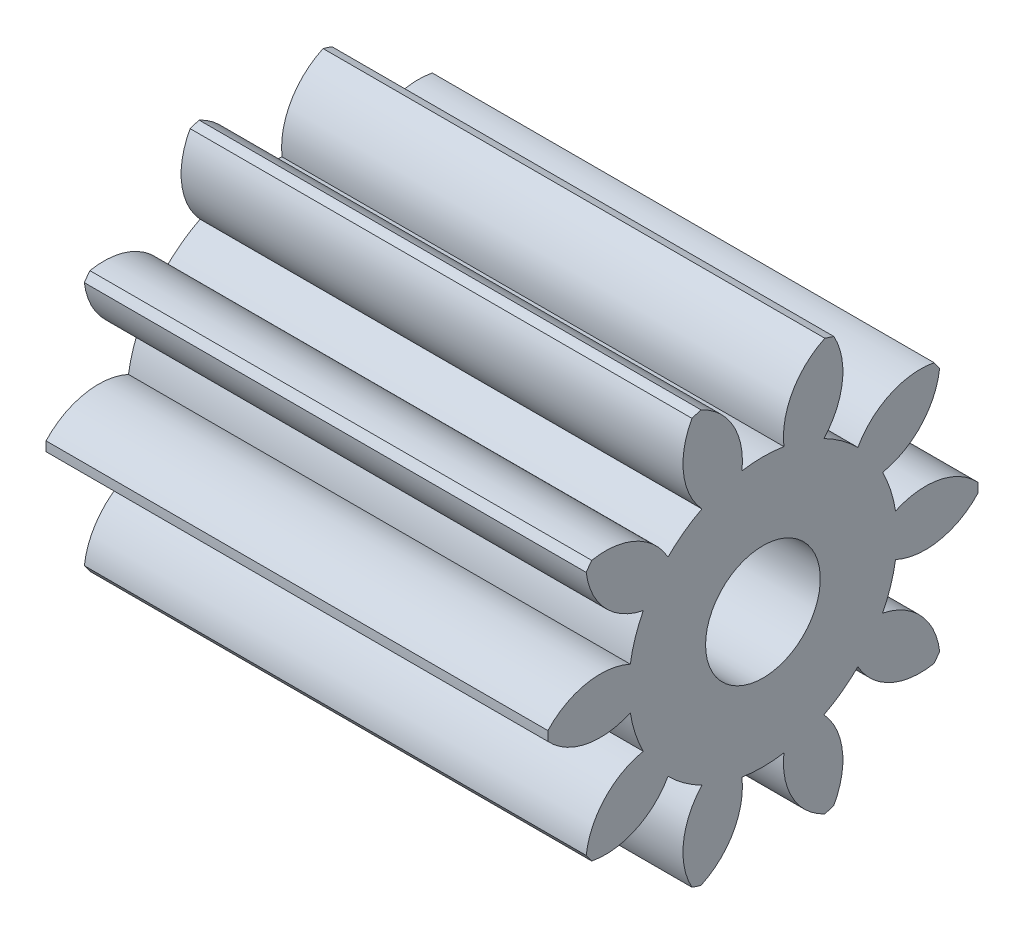
SolidWorks part; units mm, degrees
material "Простая углеродистая сталь"
ref_plane "Plane1" through (0, 0, 0) normal (0, 0, 1) x (1, 0, 0)
ref_plane "Plane2" through (0, 0, 0) normal (0, 1, 0) x (1, 0, 0)
ref_plane "Plane3" through (0, 0, 0) normal (1, 0, 0) x (0, 0, -1)
sketch "HoldingSke" plane through (0, 0, 0) normal (0, 1, 0) x (1, 0, 0)
  line L0 (0, 0) -> (3.9392, -0.6946)
  line L1 (-15, 0) -> (100, 0) construction
  line L2 (0, 0) -> (-2.1039, 2.3779)
  line L3 (0, 0) -> (-11.863, 4.5341)
  line L4 (0, 0) -> (8.5048, 1.4996)
  line L5 (0, 0) -> (-46.8476, -17.4728)
  line L6 (0, 0) -> (-2.9014, -1.9576)
  line L7 (-2.1039, 2.3779) -> (8.6586, 51.2059)
  line L8 (-76.2, 54.61) -> (-76.1, 54.61)
  line L9 (-71.009, 38.7566) -> (-53.1078, 45.2721)
  line L10 (-76.2, 71.12) -> (104.1128, 71.12)
  line L11 (0, 0) -> (-3.5, 0)
  line L12 (-76.2, 101.6) -> (-76.192, 101.6)
  line L13 (24.9733, 27.94) -> (52.9518, 28.4284)
  line L14 (24.9733, 27.94) -> (24.9743, 27.94)
  line L15 (24.9733, 27.94) -> (100.4006, 29.5858)
  line L16 (-63.627, -0.25) -> (-12.827, -0.25)
  circle A0 centre (0, 0) radius 0.4
  circle A1 centre (0, 0) radius 0.9365
  circle A2 centre (0, 0) radius 37.5
  circle A3 centre (0, 0) radius 0.4
  dimension "MHD" = 1.873
  dimension "Hub_dia" = 75
  dimension "Bore" = 0.8
  dimension "MBD" = 0.8
  dimension "Num_teeth" = 10
  dimension "Pitch" = 4
  dimension "Overall_len" = 50
  dimension "Show_teeth" = 10
  dimension "Thickness" = 3.5
  dimension "OAL" = 50.0001
  dimension "T_dim" = 0.1
  dimension "Ap" = 20
  dimension "H" = 19.05
  dimension "Pitch_radius" = 180.3128
  dimension "Width" = 3.5
  dimension "Backlash" = 0.008
  dimension "Addendum_fac" = 1
  dimension "Dedendum_fac" = 1.25
  dimension "Clearance_fac" = 0.25
  dimension "Dedendum_add" = 0.001
  dimension "Module" = 0.25
sketch "BasProSke" plane through (0, 0, 0) normal (0, 1, 0) x (1, 0, 0)
  line L0 (-10, 0) -> (60, 0) construction
  line L1 (0, 0) -> (0, 1.5)
  line L2 (0, 0) -> (3.5, 0)
  line L3 (3.5, 0) -> (3.5, 1.5)
  line L4 (3.5, 1.5) -> (0, 1.5)
  dimension "Thickness" = 3.5
  dimension "Diameter" = 3
revolve "Base-Revolve" add sketch "BasProSke" angle 360 about L0
sketch "TooCutSke" plane through (0, 0, 0) normal (1, 0, 0) x (0, 0, -1)
  line L1 (0, 0) -> (0, 107) construction
  line L2 (0, 0) -> (-0.2095, 1.2323) construction
  line L3 (0, 0) -> (-0.7644, 2.3524) construction
  line L4 (-0.2095, 1.2323) -> (-0.3822, 1.1762) construction
  arc A0 (0.1463, 0.925) -> (-0.1463, 0.925) centre (0, 0) ccw
  arc A1 (0.4686, 1.4516) -> (-0.4686, 1.4516) centre (0, 0) ccw
  circle A2 centre (0, 0) radius 1.25 construction
  circle A3 centre (0, 0) radius 1.1746 construction
  arc A4 (-0.1463, 0.925) -> (-0.4686, 1.4516) centre (-0.6429, 0.983) ccw
  arc A5 (0.4686, 1.4516) -> (0.1463, 0.925) centre (0.6429, 0.983) ccw
  dimension "Root_dia" = 1.873
  dimension "Overcut_dia" = 3.0508
  dimension "Pitch_dia" = 2.5
  dimension "Base_dia" = 2.3492
  dimension "Flank_rad" = 0.5
  dimension "Half_ang" = 18
  dimension "Half_CT" = 0.1815
extrude "ToothCut" cut sketch "TooCutSke" along normal through all
fillet "Breaks" [suppressed] radius 0.005
fillet "RootFillets" [suppressed] radius 0.0635
pattern_circular "TeethCuts" count 10 every 36 about axis through (-10, 0, 0) along (1, 0, 0) of "ToothCut", "RootFillets", "Breaks"
sketch "HubNeaOneSke" plane through (0, 0, 0) normal (-1, 0, 0) x (0, 0, 1)
  circle A0 centre (0, 0) radius 0.9365
  dimension "Diameter" = 1.873
extrude "HubNearOne" [suppressed] add sketch "HubNeaOneSke" along normal blind 46.5001
sketch "HubNeaBotSke" plane through (0, 0, 0) normal (-1, 0, 0) x (0, 0, 1)
  circle A0 centre (0, 0) radius 0.9365
  dimension "Diameter" = 1.873
extrude "HubNearBoth" [suppressed] add sketch "HubNeaBotSke" along normal blind 23.25
ref_plane "FarPln" through (3.5, 0, 0) normal (1, 0, 0) x (0, 0, -1)
sketch "HubFarSke" plane through (3.5, 0, 0) normal (1, 0, 0) x (0, 0, -1)
  circle A0 centre (0, 0) radius 0.9365
  dimension "Diameter" = 1.873
extrude "HubFar" [suppressed] add sketch "HubFarSke" along normal blind 23.25
sketch "BorSke" plane through (0, 0, 0) normal (1, 0, 0) x (0, 0, -1)
  circle A0 centre (0, 0) radius 0.4
  dimension "Diameter" = 0.8
extrude "Bore" cut sketch "BorSke" along normal mid plane 100.0001
sketch "KeySke" plane through (0, 0, 0) normal (1, 0, 0) x (0, 0, -1)
  line L0 (-0.05, 0) -> (-0.05, 0.5)
  line L1 (-0.05, 0.5) -> (0.05, 0.5)
  line L2 (0.05, 0.5) -> (0.05, 0)
  line L3 (0, 0) -> (0, 34) construction
  line L4 (-0.05, 0) -> (0.05, 0)
  dimension "Offset" = 0.5
  dimension "Width" = 0.1
extrude "Keyway" [suppressed] cut sketch "KeySke" along normal mid plane 100.0001
pattern_circular "Keyway2" [suppressed] count 2 every 90 about axis through (-10, 0, 0) along (1, 0, 0)
equation "' \"Module@HoldingSke\" = 6.35"
equation "' \"Num_teeth@HoldingSke\" = 12"
equation "' \"Ap@HoldingSke\" =  20"
equation "' \"Ap@HoldingSke\" = 20"
equation "' \"Width@HoldingSke\" = 0.5 * 25.4"
equation "' \"Hub_dia@HoldingSke\"= 1 * 25.4"
equation "' \"Hub_dia@HoldingSke\" = 1 * 25.4"
equation "' \"Overall_len@HoldingSke\" = 1.0 * 25.4"
equation "' \"Bore@HoldingSke\" = 0.75 * 25.4"
equation "' \"T_dim@HoldingSke\" = 0.1 * 25.4"
equation "' \"Width@KeySke\" = 0.25 * 25.4"
equation "' \"Show_teeth@HoldingSke\" = 13"
equation "' \"Backlash@HoldingSke\" = 0.009 * 25.4"
equation "' \"Addendum_fac@HoldingSke\" = 1.0"
equation "' \"Dedendum_fac@HoldingSke\" = 1.25"
equation "' \"Dedendum_add@HoldingSke\" = 0.00005 * 25.4"
equation "' \"Clearance_fac@HoldingSke\" = 0.25"
equation "\"Pitch@HoldingSke\" = 1 / \"Module@HoldingSke\""
equation "\"Overcut_dia@TooCutSke\" = (\"Num_teeth@HoldingSke\" + 2 * \"Addendum_fac@HoldingSke\") / \"Pitch@HoldingSke\" + 0.002 * 25.4"
equation "\"Pitch_dia@TooCutSke\" = \"Num_teeth@HoldingSke\" / \"Pitch@HoldingSke\""
equation "\"Base_dia@TooCutSke\" = \"Num_teeth@HoldingSke\" / \"Pitch@HoldingSke\" * cos((\"Ap@HoldingSke\"  * 3.14159265 / 180))"
equation "\"Root_dia@TooCutSke\" = (\"Num_teeth@HoldingSke\" + 2) / \"Pitch@HoldingSke\" - 2 * (\"Addendum_fac@HoldingSke\" + \"Dedendum_fac@HoldingSke\") / \"Pitch@HoldingSke\" - \"Dedendum_add@HoldingSke\" * 2"
equation "\"Half_ang@TooCutSke\" = 180 / \"Num_teeth@HoldingSke\""
equation "\"Half_CT@TooCutSke\" = \"Num_teeth@HoldingSke\" / \"Pitch@HoldingSke\" * sin((3.14159265 / 2 / \"Num_teeth@HoldingSke\")) / 2 - 7 * \"Backlash@HoldingSke\" / 4"
equation "\"Flank_rad@TooCutSke\" = \"Num_teeth@HoldingSke\" / \"Pitch@HoldingSke\" / 5"
equation "\"Radius@RootFillets\" = \"Clearance_fac@HoldingSke\" / \"Pitch@HoldingSke\" + \"Dedendum_add@HoldingSke\""
equation "\"Break_rad@Breaks\" = 0.02 / \"Pitch@HoldingSke\""
equation "\"Thickness@HoldingSke\" = \"Width@HoldingSke\""
equation "\"OAL@HoldingSke\" = \"Thickness@HoldingSke\""
equation "\"MHD@HoldingSke\" = (\"Num_teeth@HoldingSke\" + 2) / \"Pitch@HoldingSke\" - 2 * (\"Addendum_fac@HoldingSke\" + \"Dedendum_fac@HoldingSke\")  / \"Pitch@HoldingSke\" - \"Dedendum_add@HoldingSke\" * 2"
equation "\"MBD@HoldingSke\" = (\"Num_teeth@HoldingSke\" + 2) / \"Pitch@HoldingSke\" - 2 * (\"Addendum_fac@HoldingSke\" + \"Dedendum_fac@HoldingSke\")  / \"Pitch@HoldingSke\" - \"Dedendum_add@HoldingSke\" * 2 - 0.002 * 25.4"
equation "\"MHD@HoldingSke\" = ((sgn( \"MHD@HoldingSke\" - \"Hub_dia@HoldingSke\" )-1)*( \"MHD@HoldingSke\" - \"Hub_dia@HoldingSke\" ))/-2+ \"Hub_dia@HoldingSke\""
equation "\"MBD@HoldingSke\" = ((sgn( \"MBD@HoldingSke\" - \"Bore@HoldingSke\" )-1)*( \"MBD@HoldingSke\" - \"Bore@HoldingSke\" ))/-2+ \"Bore@HoldingSke\""
equation "\"OAL@HoldingSke\" = ((sgn( \"OAL@HoldingSke\" - \"Overall_len@HoldingSke\" )+1)*( \"OAL@HoldingSke\" - \"Overall_len@HoldingSke\" ))/2 + \"Overall_len@HoldingSke\" + 0.000002 * 25.4"
equation "\"Num_teeth@TeethCuts\" = int( \"Show_teeth@HoldingSke\" ) + 1"
equation "\"Num_teeth@TeethCuts\" = ((sgn( \"Num_teeth@TeethCuts\" - \"Num_teeth@HoldingSke\" )-1)*( \"Num_teeth@TeethCuts\" - \"Num_teeth@HoldingSke\" ))/-2+ \"Num_teeth@HoldingSke\""
equation "\"Num_teeth@TeethCuts\" = ((sgn( \"Num_teeth@TeethCuts\" - 2.0)+1)*( \"Num_teeth@TeethCuts\" - 2.0))/2 +2.0"
equation "\"Angle@TeethCuts\" = 360.0 / \"Num_teeth@HoldingSke\""
equation "\"Diameter@BasProSke\" = (\"Num_teeth@HoldingSke\" + 2 * \"Addendum_fac@HoldingSke\") / \"Pitch@HoldingSke\""
equation "\"Thickness@BasProSke\"  = \"Thickness@HoldingSke\""
equation "' \"Fillet_rad@BasProSke\" =  \"Thickness@HoldingSke\" * 0.05"
equation "' \"Fillet_rad@BasProSke\" = \"Thickness@HoldingSke\" * 0.05"
equation "\"MHD@HoldingSke\" = ((sgn( \"MHD@HoldingSke\" - \"Root_dia@TooCutSke\" )-1)*( \"MHD@HoldingSke\" - \"Root_dia@TooCutSke\" ))/-2+ \"Root_dia@TooCutSke\""
equation "\"Diameter@HubNeaOneSke\" = \"MHD@HoldingSke\""
equation "\"Length@HubNearOne\" = \"OAL@HoldingSke\" - \"Thickness@BasProSke\""
equation "\"Diameter@HubNeaBotSke\" = \"MHD@HoldingSke\""
equation "\"Length@HubNearBoth\" = ( \"OAL@HoldingSke\" - \"Thickness@BasProSke\" ) / 2.0"
equation "\"Thickness@FarPln\" = \"Thickness@BasProSke\""
equation "\"Diameter@HubFarSke\" = \"MHD@HoldingSke\""
equation "\"Length@HubFar\" = ( \"OAL@HoldingSke\" - \"Thickness@BasProSke\" ) / 2.0"
equation "\"Diameter@BorSke\" = \"MBD@HoldingSke\""
equation "\"D1@Bore\" = \"OAL@HoldingSke\" * 2.0"
equation "\"D1@Keyway\" = \"OAL@HoldingSke\" * 2.0"
equation "\"Offset@KeySke\" = \"T_dim@HoldingSke\" + \"MBD@HoldingSke\" / 2.0"
